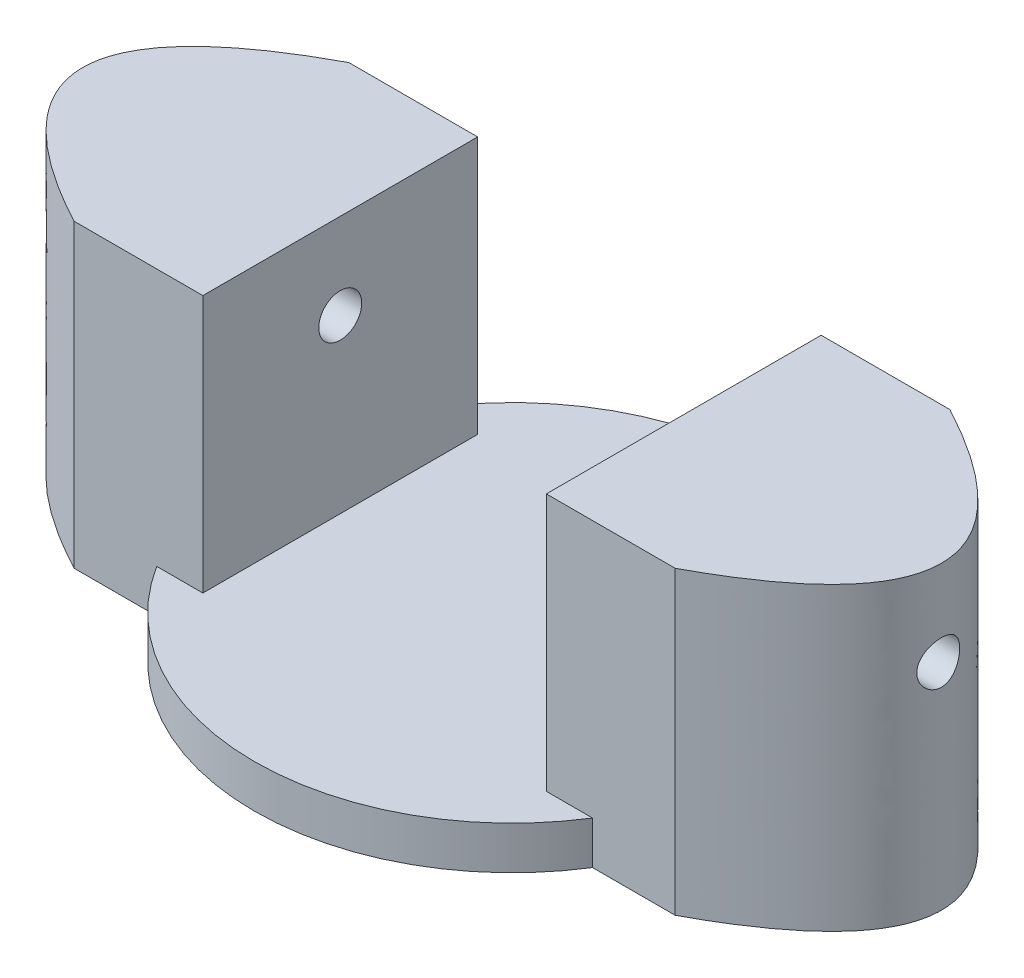
SolidWorks part; units mm, degrees
ref_plane "Front Plane" through (0, 0, 0) normal (0, 0, 1) x (1, 0, 0)
ref_plane "Top Plane" through (0, 0, 0) normal (0, 1, 0) x (1, 0, 0)
ref_plane "Right Plane" through (0, 0, 0) normal (1, 0, 0) x (0, 0, -1)
sketch "Sketch1" plane through (0, 0, 0) normal (0, 1, 0) x (1, 0, 0)
  circle A0 centre (0, 0) radius 25
  dimension "D1" = 50
extrude "Boss-Extrude1" add sketch "Sketch1" against normal blind 25
sketch "Sketch2" plane through (0, 0, 0) normal (0, 1, 0) x (1, 0, 0)
  circle A0 centre (0, 0) radius 150
  dimension "D1" = 300
extrude "Boss-Extrude2" add sketch "Sketch2" along normal blind 25
sketch "Sketch3" plane through (0, 25, 0) normal (0, 1, 0) x (1, 0, 0)
  line L13 (250, 80) -> (100, 80)
  line L14 (100, -80) -> (100, 80)
  line L15 (250, -80) -> (100, -80)
  line L20 (-250, -80) -> (-250, 80)
  line L21 (-250, -80) -> (-100, -80)
  line L22 (250, -80) -> (250, 80)
  line L23 (-100, -80) -> (-100, 80)
  line L24 (-250, 80) -> (-100, 80)
extrude "Boss-Extrude3" add sketch "Sketch3" along normal blind 150 and the other way up to surface other way up to face at (0, 0, 25)
sketch "Sketch6" plane through (-100, 0, 0) normal (1, 0, 0) x (0, 0, -1)
  line L0 (0, 125) -> (0, 25) construction
  line L2 (-76.5217, 20.8161) -> (-80, 25)
  line L3 (-80, 25) -> (80, 25) construction
  circle A0 centre (0, 125) radius 12.5
  dimension "D1" = 25
  dimension "D2" = 100
extrude "Cut-Extrude2" cut sketch "Sketch6" against normal through all and the other way through all contours A0
sketch "Sketch7" plane through (0, 175, 0) normal (0, 1, 0) x (1, 0, 0)
  line L0 (175, 80) -> (250, 80)
  line L6 (250, 80) -> (100, 80) construction
  line L7 (100, -80) -> (250, -80) construction
  line L8 (-100, 80) -> (-250, 80) construction
  line L9 (-250, -80) -> (-100, -80) construction
  line L11 (250, 80) -> (250, -80)
  line L12 (250, -80) -> (175, -80)
  line L13 (-175, -80) -> (-250, -80)
  line L14 (-250, -80) -> (-250, 80)
  line L15 (-250, 80) -> (-175, 80)
  spline S0 degree 2 poles (175, 80) (325, 0) (175, -80) knots 0 0 0 1 1 1
  spline S1 degree 2 poles (-175, 80) (-325, 0) (-175, -80) knots 0 0 0 1 1 1
  line M6 (250, -80) -> (250, 80)
  line M7 (250, 80) -> (100, 80)
  line M9 (100, -80) -> (250, -80)
extrude "Cut-Extrude3" cut sketch "Sketch7" against normal through all contours S1 L14 L13 | S1 L15 L14 | S0 M6 M9 | S0 L11 M7
ref_plane "Plane2" through (0, 0, -150) normal (0, 0, -1) x (-1, 0, 0)
sketch "Sketch9" plane through (0, 0, -150) normal (0, 0, -1) x (-1, 0, 0)
  line L0 (0, 25) -> (0, 30) construction
  line L1 (126.8858, 25) -> (-126.8858, 25) construction
  circle A0 centre (0, 30) radius 5
  dimension "D1" = 5
extrude "Boss-Extrude5" add sketch "Sketch9" along normal blind 10 and the other way blind 10 separate body
